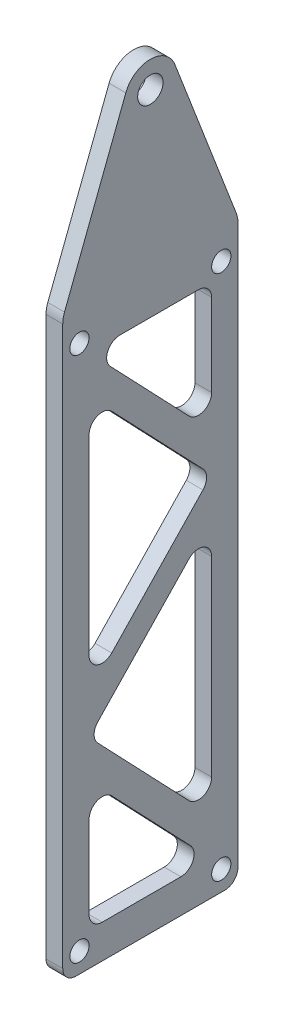
SolidWorks part; units mm, degrees
material "6061 Alloy"
ref_plane "Front Plane" through (0, 0, 0) normal (0, 0, 1) x (1, 0, 0)
ref_plane "Top Plane" through (0, 0, 0) normal (0, 1, 0) x (1, 0, 0)
ref_plane "Right Plane" through (0, 0, 0) normal (1, 0, 0) x (0, 0, -1)
sketch "Sketch1" plane through (0, 0, 0) normal (1, 0, 0) x (0, 0, -1)
  line L0 (-13.4747, 0) -> (13.4747, 0) construction
  line L1 (0, 0) -> (0, 35) construction
  line L2 (-13.4747, 0) -> (0, 35) construction
  line L3 (0, 35) -> (13.4747, 0) construction
  line L4 (13.4747, 0) -> (-13.4747, 0) construction
  line L5 (20.7574, -5) -> (-20.7574, -5)
  line L6 (-20.7574, -5) -> (0, 48.9165)
  line L7 (0, 48.9165) -> (20.7574, -5)
  line L8 (-13.4747, 0) -> (13.4747, 0) construction
  line L9 (-13.4747, 0) -> (-13.4747, -100) construction
  line L10 (13.4747, 0) -> (13.4747, -100) construction
  line L11 (-13.4747, -100) -> (13.4747, -100) construction
  line L12 (-20.7574, -5) -> (20.7574, -5)
  line L13 (-20.7574, -5) -> (-20.7574, -103.81)
  line L14 (20.7574, -5) -> (20.7574, -103.81)
  line L15 (-20.7574, -103.81) -> (20.7574, -103.81)
  circle A0 centre (-13.4747, 0) radius 1.8288
  circle A1 centre (0, 35) radius 2.413
  circle A2 centre (13.4747, 0) radius 1.8288
  circle A3 centre (-13.4747, -100) radius 1.8288
  circle A4 centre (13.4747, -100) radius 1.8288
  point P4 (0, 0)
  dimension "D3" = 3.6576
  dimension "D4" = 4.826
  dimension "D1" = 26.9494
  dimension "D5" = 100
  dimension "D6" = 3.81
  dimension "D7" = 35
  dimension "D2" = 5
extrude "Boss-Extrude1" add sketch "Sketch1" along normal blind 3.175 contours L13 L15 L14 L5 A4 A3 | L7 L6 L5 A2 A1 A0
sketch "Sketch2" plane through (3.175, 0, 0) normal (1, 0, 0) x (0, 0, -1)
  line L3 (-11.645, -97.42) -> (-11.645, -2.5) construction
  line L4 (11.645, -97.42) -> (11.645, -2.5) construction
  line L5 (-11.645, -2.5) -> (11.645, -2.5) construction
  line L6 (-11.645, -97.42) -> (11.645, -97.42) construction
  line L7 (-20.7574, -5) -> (-20.7574, -103.81) construction
  line L9 (11.645, -2.5) -> (-11.645, -2.5)
  line L10 (-11.645, -2.5) -> (11.645, -26.8987)
  line L11 (11.645, -26.8987) -> (11.645, -2.5)
  line L12 (-11.645, -9.7413) -> (11.645, -34.14)
  line L13 (11.645, -34.14) -> (-11.645, -58.5387)
  line L14 (-11.645, -58.5387) -> (-11.645, -34.14)
  line L15 (11.645, -37.7607) -> (-11.645, -62.1593) construction
  line L16 (-11.645, -34.14) -> (-11.645, -9.7413)
  line L17 (-11.645, -73.0213) -> (-11.645, -97.42)
  line L18 (-11.645, -97.42) -> (11.645, -97.42)
  line L19 (11.645, -97.42) -> (-11.645, -73.0213)
  line L20 (11.645, -41.3813) -> (11.645, -65.78)
  line L21 (11.645, -65.78) -> (11.645, -90.1787)
  line L22 (11.645, -90.1787) -> (-11.645, -65.78)
  line L23 (-11.645, -65.78) -> (11.645, -41.3813)
  line L24 (-16.645, -1051.4901) -> (-16.645, 48948.5099) construction
  line L25 (16.645, -1047.4882) -> (16.645, 48952.5118) construction
  line L26 (-20.7574, -5) -> (-16.645, -5) construction
  line L27 (20.7574, -5) -> (16.645, -5) construction
  line L28 (-16.645, -103.81) -> (-16.645, 37.413)
  line L29 (-16.645, -103.81) -> (-20.7574, -103.81)
  line L30 (-16.645, 37.413) -> (-20.7574, 37.413)
  line L31 (-20.7574, -103.81) -> (-20.7574, 37.413)
  line L32 (-20.7574, -103.81) -> (20.7574, -103.81) construction
  line L33 (16.645, -103.81) -> (16.645, 37.413)
  line L34 (16.645, -103.81) -> (20.7574, -103.81)
  line L35 (16.645, 37.413) -> (20.7574, 37.413)
  line L36 (20.7574, -103.81) -> (20.7574, 37.413)
  circle A1 centre (13.4747, 0) radius 1.8288 construction
  circle A2 centre (0, 35) radius 2.413 construction
  circle A3 centre (13.4747, -100) radius 1.8288 construction
  point P0 (11.645, -49.96)
  point P2 (0, -97.42)
  point P28 (0, -49.96)
  point P41 (11.645, -26.8987)
  point P44 (0, 0)
  dimension "D4" = 2.58
  dimension "D1" = 33.29
  dimension "D2" = 5
  dimension "D3" = 2.5
  dimension "D5" = 5
  dimension "D6" = 2.5
  dimension "D7" = 2
  dimension "D8" = 5
extrude "Cut-Extrude1" cut sketch "Sketch2" against normal through all
fillet "Fillet1" radius 2.5 14 edges at (1.5875, -97.42, -11.645) (1.5875, -90.1787, -11.645) (1.5875, -41.3813, -11.645) (1.5875, -73.0213, 11.645) (1.5875, -97.42, 11.645) (1.5875, -65.78, 11.645) (1.5875, -58.5387, 11.645) (1.5875, -34.14, -11.645) (1.5875, -9.7413, 11.645) (1.5875, -2.5, 11.645) (1.5875, -26.8987, -11.645) (1.5875, -2.5, -11.645) (1.5875, -103.81, 16.645) (1.5875, -103.81, -16.645)
fillet "Fillet2" radius 5 3 edges at (1.5875, 48.9165, 0) (1.5875, 5.6818, 16.645) (1.5875, 5.6818, -16.645)
